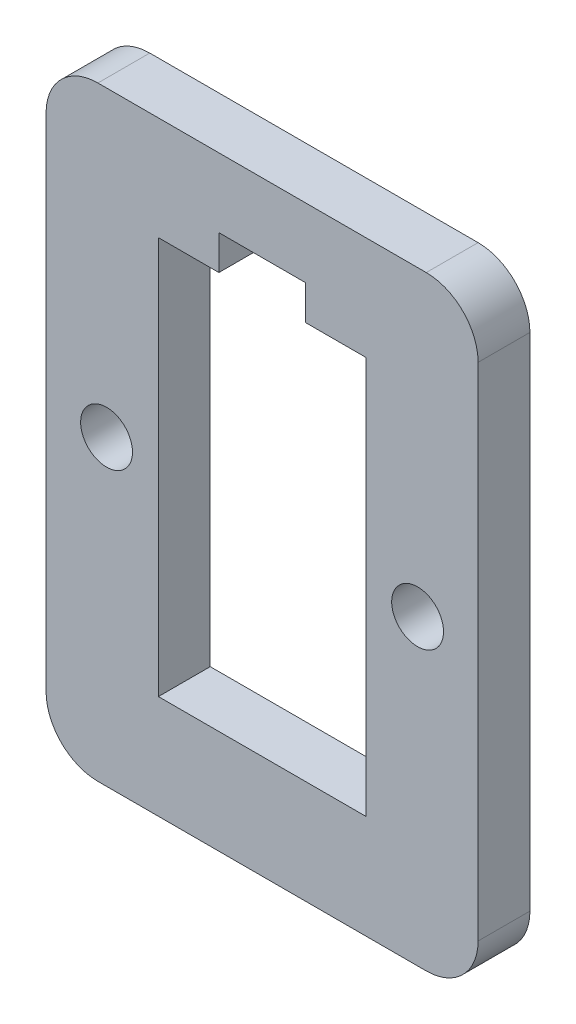
SolidWorks part; units mm, degrees
ref_plane "前基準面" through (0, 0, 0) normal (0, 0, 1) x (1, 0, 0)
ref_plane "上基準面" through (0, 0, 0) normal (0, 1, 0) x (1, 0, 0)
ref_plane "右基準面" through (0, 0, 0) normal (1, 0, 0) x (0, 0, -1)
sketch "草圖1" plane through (0, 0, 0) normal (0, 0, 1) x (1, 0, 0)
  line L0 (170.5002, 77) -> (170.5002, 100) construction
  line L1 (170.5002, 100) -> (167.0002, 100) construction
  line L2 (167.0002, 100) -> (167.0002, 102.0001) construction
  line L3 (167.0002, 102.0001) -> (162.0002, 102.0001) construction
  line L4 (162.0002, 102.0001) -> (162.0002, 100) construction
  line L5 (162.0002, 100) -> (158.5002, 100) construction
  line L6 (158.5002, 100) -> (158.5002, 77) construction
  line L7 (158.5002, 77) -> (170.5002, 77) construction
  line L8 (155.0002, 71) -> (174.0002, 71) construction
  line L9 (170.5002, 77) -> (170.5002, 100)
  line L10 (170.5002, 100) -> (167.0002, 100)
  line L11 (167.0002, 100) -> (167.0002, 102.0001)
  line L12 (167.0002, 102.0001) -> (162.0002, 102.0001)
  line L13 (162.0002, 102.0001) -> (162.0002, 100)
  line L14 (162.0002, 100) -> (158.5002, 100)
  line L15 (158.5002, 100) -> (158.5002, 77)
  line L16 (158.5002, 77) -> (170.5002, 77)
  line L17 (155.0002, 71) -> (174.0002, 71)
  line L18 (152.0002, 103) -> (152.0002, 74)
  line L19 (177.0002, 74) -> (177.0002, 103)
  line L20 (155.0002, 106) -> (174.0002, 106)
  circle A0 centre (155.5002, 88.5) radius 1.5 construction
  circle A1 centre (173.5002, 88.5) radius 1.5 construction
  arc A2 (174.0002, 71) -> (177.0002, 74) centre (174.0002, 74) ccw construction
  arc A3 (152.0002, 74) -> (155.0002, 71) centre (155.0002, 74) ccw construction
  arc A4 (177.0002, 103) -> (174.0002, 106) centre (174.0002, 103) ccw construction
  arc A5 (155.0002, 106) -> (152.0002, 103) centre (155.0002, 103) ccw construction
  circle A6 centre (155.5002, 88.5) radius 1.5
  circle A7 centre (173.5002, 88.5) radius 1.5
  arc A8 (174.0002, 71) -> (177.0002, 74) centre (174.0002, 74) ccw
  arc A9 (152.0002, 74) -> (155.0002, 71) centre (155.0002, 74) ccw
  arc A10 (177.0002, 103) -> (174.0002, 106) centre (174.0002, 103) ccw
  arc A11 (155.0002, 106) -> (152.0002, 103) centre (155.0002, 103) ccw
extrude "填料-伸長1" add sketch "草圖1" along normal blind 3
